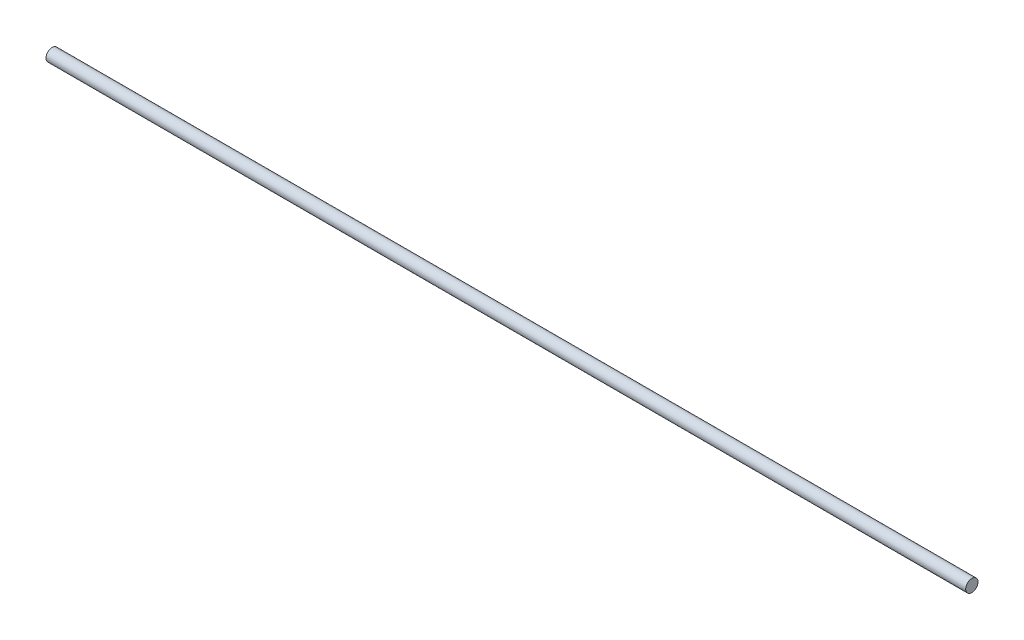
SolidWorks part; units mm, degrees
ref_plane "Front Plane" through (0, 0, 0) normal (1, 0, 0) x (0, 1, 0)
ref_plane "Top Plane" through (0, 0, 0) normal (0, 0, 1) x (0, 1, 0)
ref_plane "Right Plane" through (0, 0, 0) normal (0, 1, 0) x (-1, 0, 0)
sketch "Sketch2" plane through (0, 0, 0) normal (1, 0, 0) x (0, 1, 0)
  circle A0 centre (0, 0) radius 10.033
  dimension "D1" = 20.066
extrude "Boss-Extrude1" add sketch "Sketch2" along normal mid plane 1500
